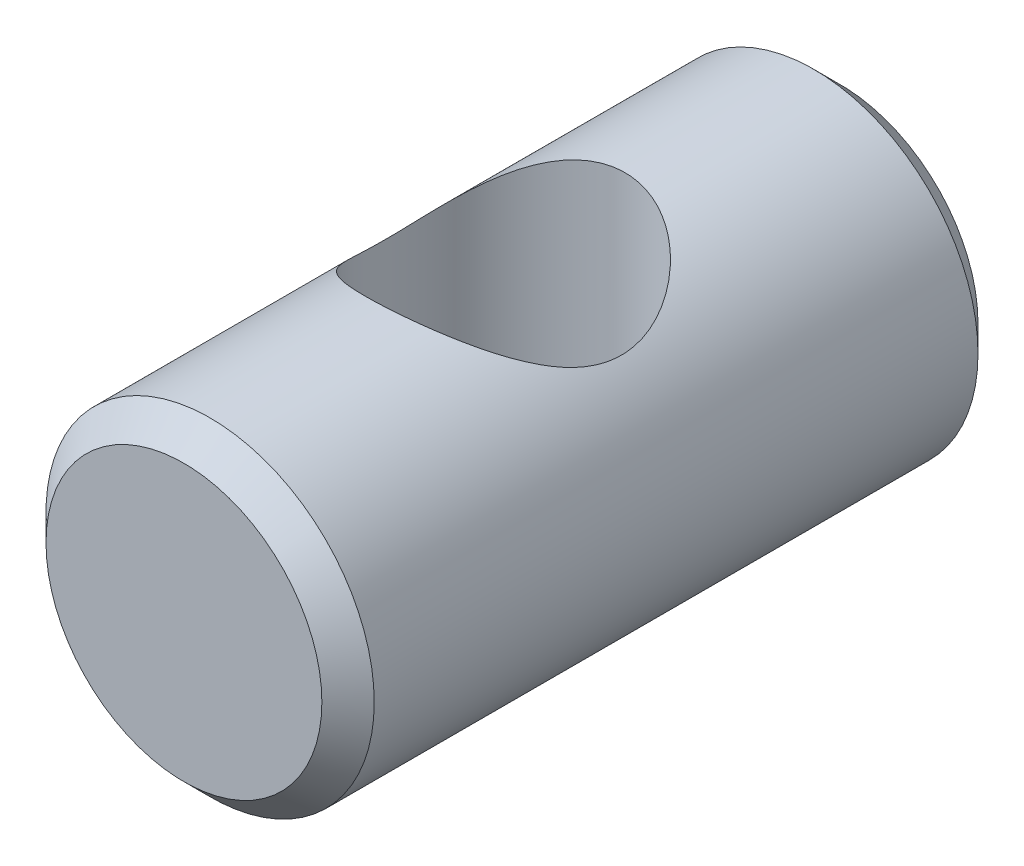
SolidWorks part; units mm, degrees
ref_plane "Front Plane" through (0, 0, 0) normal (0, 0, 1) x (1, 0, 0)
ref_plane "Top Plane" through (0, 0, 0) normal (0, 1, 0) x (1, 0, 0)
ref_plane "Right Plane" through (0, 0, 0) normal (1, 0, 0) x (0, 0, -1)
sketch "Sketch1" plane through (0, 0, 0) normal (0, 0, 1) x (1, 0, 0)
  circle A0 centre (0, 0) radius 4.765
  dimension "D1" = 9.53
extrude "Boss-Extrude1" add sketch "Sketch1" along normal mid plane 19.05
sketch "Sketch2" plane through (0, 0, 0) normal (0, 1, 0) x (1, 0, 0)
  circle A0 centre (-0.25, 0) radius 3.43
  dimension "D1" = 6.86
  dimension "D2" = 0.25
extrude "Cut-Extrude1" cut sketch "Sketch2" against normal through all both and the other way through all
chamfer "Chamfer1" distance 0.76 angle 45 2 edges at (4.765, 0, 9.525) (4.765, 0, -9.525)
